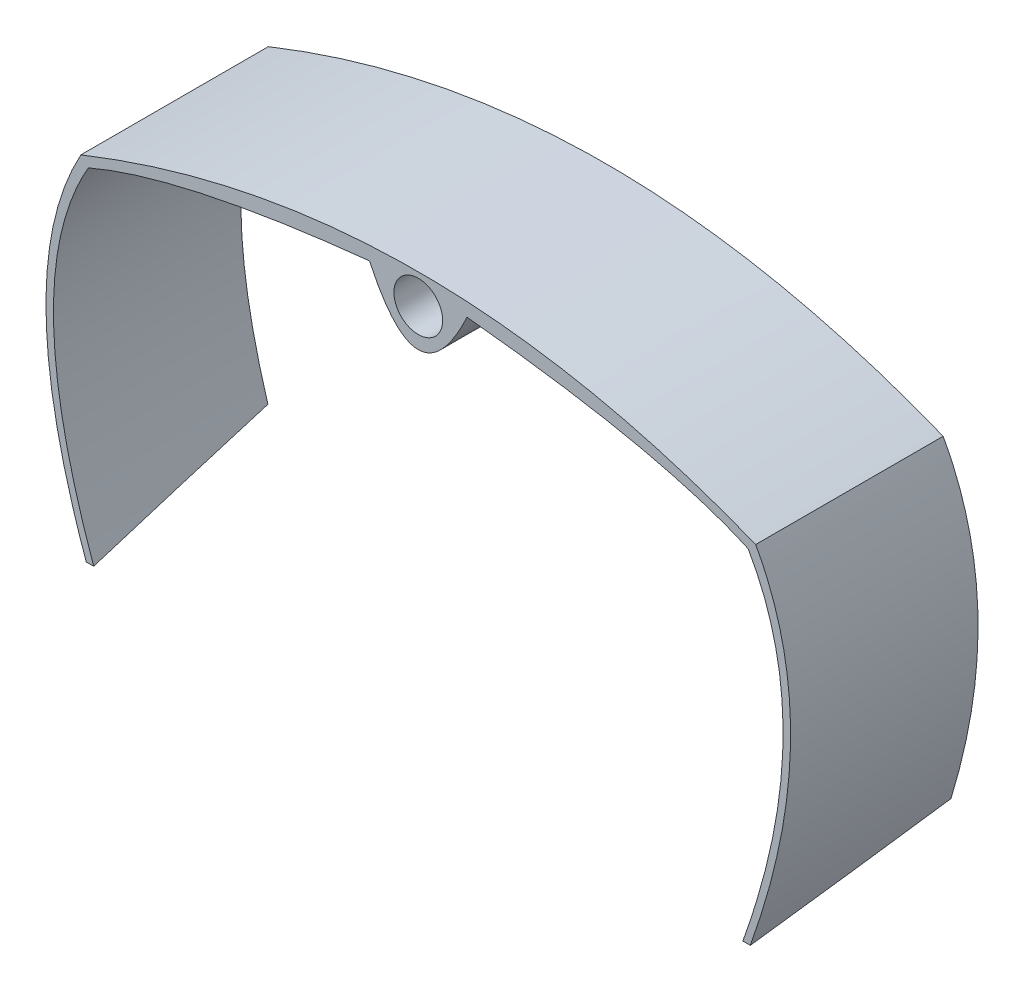
SolidWorks part; units mm, degrees
ref_plane "Front Plane" through (0, 0, 0) normal (0, 0, 1) x (1, 0, 0)
ref_plane "Top Plane" through (0, 0, 0) normal (0, 1, 0) x (1, 0, 0)
ref_plane "Right Plane" through (0, 0, 0) normal (1, 0, 0) x (0, 0, -1)
sketch "草圖1" plane through (0, 0, 0) normal (0, 0, 1) x (1, 0, 0)
  line L0 (-45, -5) -> (0, 13) construction
  line L1 (0, 13) -> (45, -5) construction
  line L4 (-6.5, 2) -> (0, -12) construction
  line L5 (0, -12) -> (6.5, 2) construction
  line L6 (6.5, 2) -> (32.2287, -0.6164) construction
  line L7 (32.2287, -0.6164) -> (44, -6) construction
  line L8 (-6.5, 2) -> (-31.608, -0.6164) construction
  line L9 (-31.608, -0.6164) -> (-44, -6) construction
  line L10 (-45, -5) -> (-56, -25) construction
  line L11 (-56, -25) -> (-41, -60) construction
  line L12 (45, -5) -> (56, -25) construction
  line L13 (56, -25) -> (41, -60) construction
  line L14 (-44, -6) -> (-55, -25) construction
  line L15 (-55, -25) -> (-40, -60) construction
  line L16 (44, -6) -> (55, -25) construction
  line L17 (55, -25) -> (40, -60) construction
  line L18 (-41, -60) -> (-40, -60)
  line L19 (40, -60) -> (41, -60)
  circle A0 centre (0, 0) radius 3.25
  spline S0 degree 2 poles (-45, -5) (0, 13) (45, -5) knots 0 0 0 1 1 1
  spline S1 degree 2 poles (-6.5, 2) (0, -12) (6.5, 2) knots 0 0 0 1 1 1
  spline S2 degree 2 poles (6.5, 2) (32.2287, -0.6164) (44, -6) knots 0 0 0 1 1 1
  spline S3 degree 2 poles (-6.5, 2) (-31.608, -0.6164) (-44, -6) knots 0 0 0 1 1 1
  spline S4 degree 2 poles (-45, -5) (-56, -25) (-41, -60) knots 0 0 0 1 1 1
  spline S5 degree 2 poles (45, -5) (56, -25) (41, -60) knots 0 0 0 1 1 1
  spline S6 degree 2 poles (-44, -6) (-55, -25) (-40, -60) knots 0 0 0 1 1 1
  spline S7 degree 2 poles (44, -6) (55, -25) (40, -60) knots 0 0 0 1 1 1
  dimension "D1" = 6.5
  dimension "D2" = 90
  dimension "D3" = 45
  dimension "D4" = 13
  dimension "D5" = 1
  dimension "D6" = 12
  dimension "D7" = 6.5
  dimension "D8" = 6.5
  dimension "D9" = 32.2287
  dimension "D10" = 31.608
  dimension "D11" = 1
  dimension "D12" = 1
  dimension "D13" = 1
  dimension "D14" = 40
  dimension "D15" = 40
  dimension "D16" = 55
  dimension "D17" = 55
  dimension "D18" = 25
  dimension "D19" = 60
  dimension "D20" = 44
  dimension "D21" = 44
  dimension "D22" = 6
  dimension "D23" = 5
  dimension "D24" = 2
extrude "填料-伸長1" add sketch "草圖1" along normal blind 25
sketch "草圖2" plane through (0, 0, 0) normal (1, 0, 0) x (0, 0, -1)
  line L0 (-28.9063, -52.4923) -> (4.0672, -45.4684)
  line L5 (4.0672, -45.4684) -> (5.936, -63.0839)
  line L6 (5.936, -63.0839) -> (-26.9012, -70.5715)
  line L7 (-26.9012, -70.5715) -> (-30.3849, -68.3815)
  line L8 (-28.9063, -52.4923) -> (-30.3849, -68.3815)
extrude "除料-伸長1" cut sketch "草圖2" against normal through all and the other way through all
